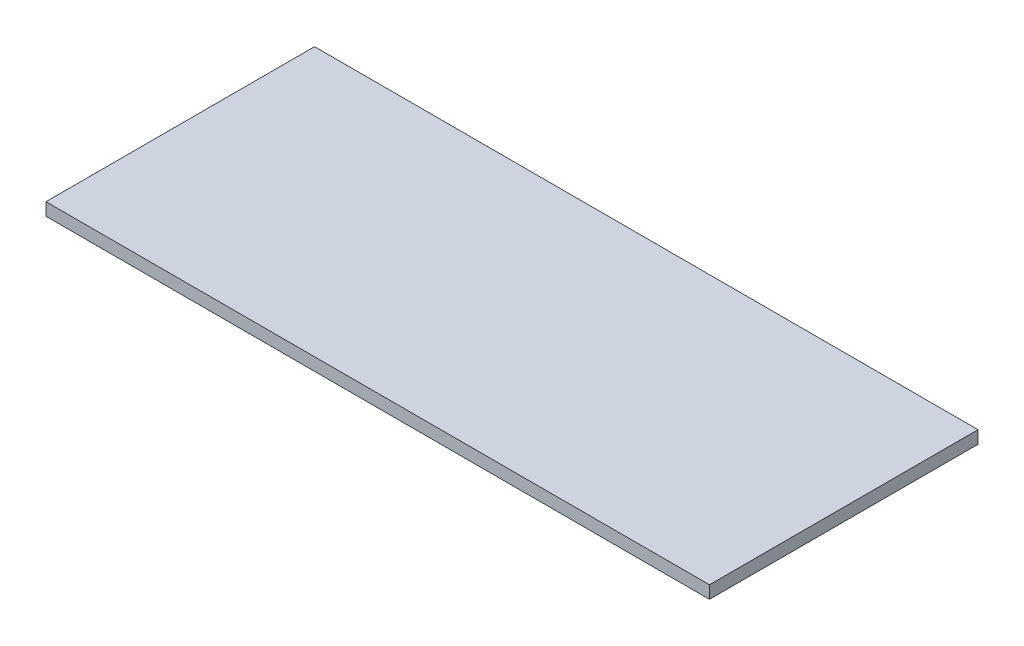
SolidWorks part; units mm, degrees
ref_plane "Front Plane" through (0, 0, 0) normal (0, 0, 1) x (1, 0, 0)
ref_plane "Top Plane" through (0, 0, 0) normal (0, 1, 0) x (1, 0, 0)
ref_plane "Right Plane" through (0, 0, 0) normal (1, 0, 0) x (0, 0, -1)
sketch "Sketch1" plane through (0, 0, 0) normal (0, 1, 0) x (1, 0, 0)
  line L1 (-1050, 425) -> (1050, 425)
  line L2 (-1050, 425) -> (-1050, -425)
  line L3 (-1050, -425) -> (1050, -425)
  line L4 (1050, 425) -> (1050, -425)
  dimension "D1" = 2100
  dimension "D2" = 850
  dimension "D3" = 1050
  dimension "D4" = 425
extrude "Boss-Extrude1" add sketch "Sketch1" along normal blind 40
